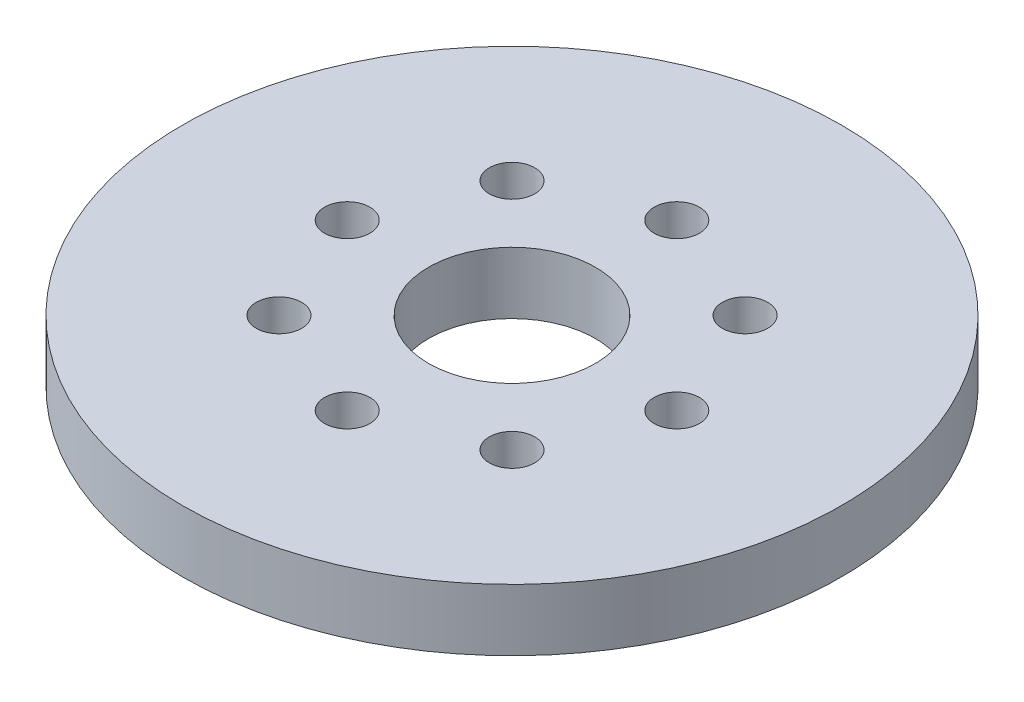
SolidWorks part; units mm, degrees
material "ABS PC"
ref_plane "Front Plane" through (0, 0, 0) normal (0, 0, 1) x (1, 0, 0)
ref_plane "Top Plane" through (0, 0, 0) normal (0, 1, 0) x (1, 0, 0)
ref_plane "Right Plane" through (0, 0, 0) normal (1, 0, 0) x (0, 0, -1)
sketch "Sketch1" plane through (0, 0, 0) normal (0, 1, 0) x (1, 0, 0)
  circle A1 centre (0, 0) radius 4.05
  circle A2 centre (0, 0) radius 16
  circle A3 centre (0, 8) radius 1.1
  circle A4 centre (5.6569, 5.6569) radius 1.1
  circle A5 centre (8, 0) radius 1.1
  circle A6 centre (5.6569, -5.6569) radius 1.1
  circle A7 centre (0, -8) radius 1.1
  circle A8 centre (-5.6569, -5.6569) radius 1.1
  circle A9 centre (-8, 0) radius 1.1
  circle A10 centre (-5.6569, 5.6569) radius 1.1
  point P1 (0, 8.2184)
  dimension "D1" = 8
  dimension "D2" = 8
  dimension "D3" = 8.1
  dimension "D4" = 2.2
extrude "Boss-Extrude1" add sketch "Sketch1" along normal blind 3
